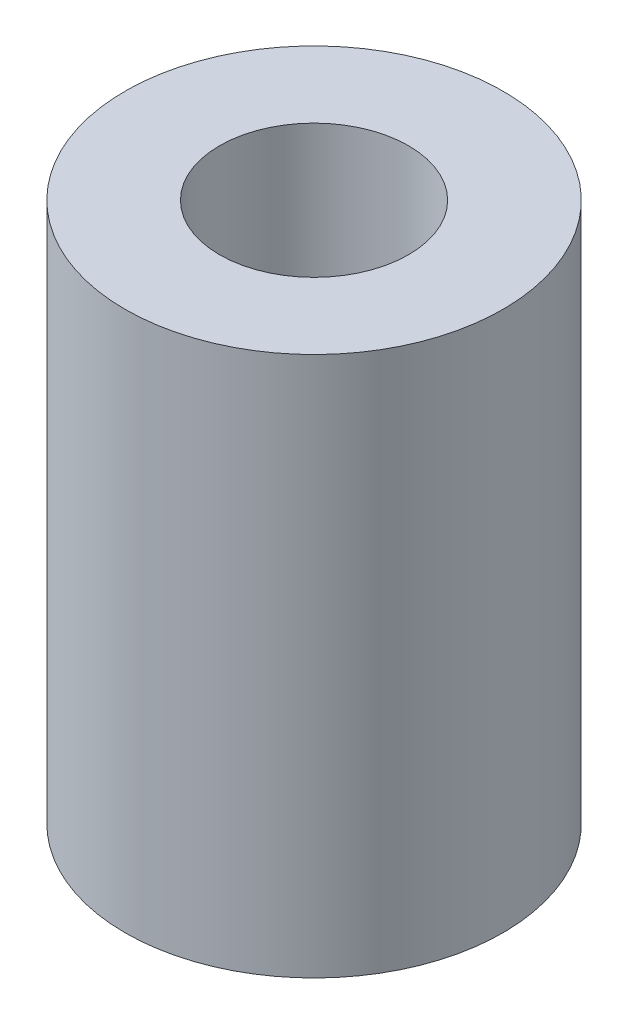
SolidWorks part; units mm, degrees
material "6061 Alloy"
ref_plane "Front Plane" through (0, 0, 0) normal (0, 0, 1) x (1, 0, 0)
ref_plane "Top Plane" through (0, 0, 0) normal (0, 1, 0) x (1, 0, 0)
ref_plane "Right Plane" through (0, 0, 0) normal (1, 0, 0) x (0, 0, -1)
sketch "Sketch1" plane through (0, 0, 0) normal (0, 1, 0) x (1, 0, 0)
  circle A0 centre (0, 0) radius 3.5
  circle A1 centre (0, 0) radius 1.75
  dimension "D1" = 3.5
  dimension "D2" = 7
extrude "Boss-Extrude1" add sketch "Sketch1" along normal blind 10
